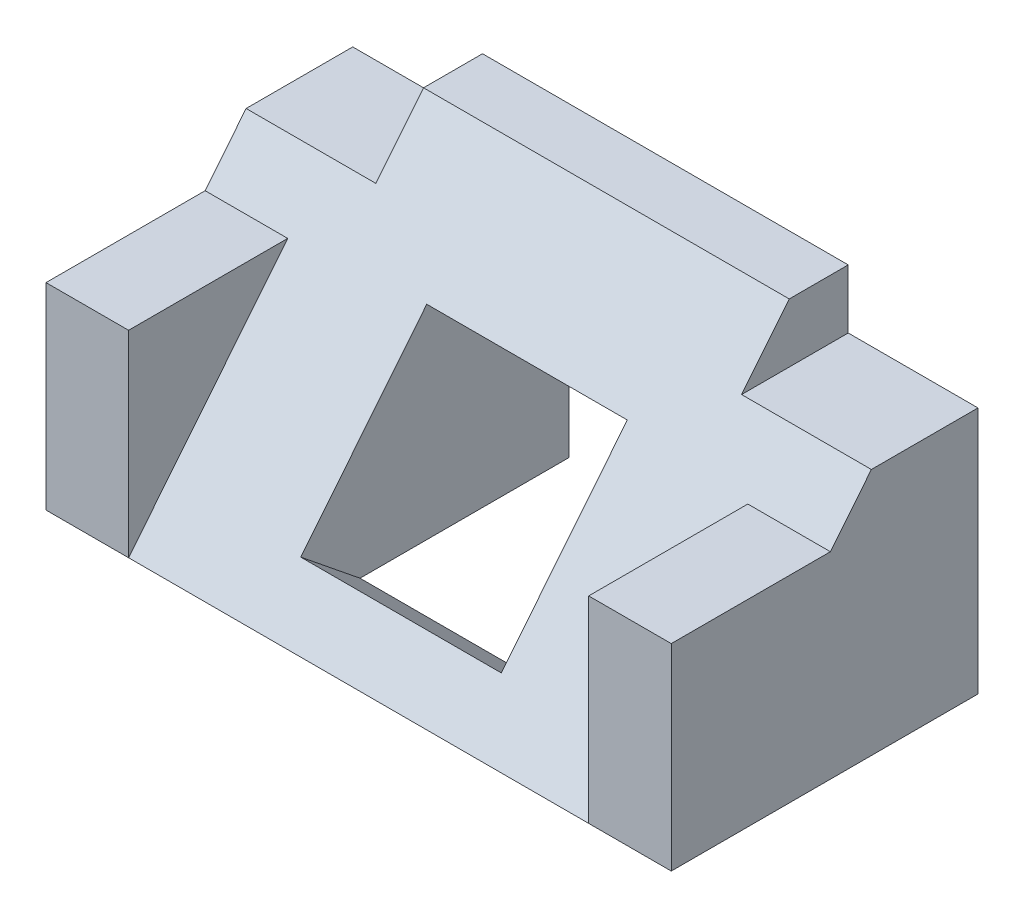
SolidWorks part; units mm, degrees
ref_plane "Front Plane" through (0, 0, 0) normal (0, 0, 1) x (1, 0, 0)
ref_plane "Top Plane" through (0, 0, 0) normal (0, 1, 0) x (1, 0, 0)
ref_plane "Right Plane" through (0, 0, 0) normal (1, 0, 0) x (0, 0, -1)
sketch "Sketch1" plane through (0, 0, 0) normal (1, 0, 0) x (0, 0, -1)
  line L0 (-330.2, -266.7) -> (203.2, 393.7)
  line L1 (100.6231, 266.7) -> (330.2, 266.7)
  line L3 (-330.2, -266.7) -> (330.2, -266.7)
  line L4 (330.2, 266.7) -> (330.2, -266.7)
  line L7 (203.2, 393.7) -> (330.2, 393.7)
  line L9 (203.2, 266.7) -> (330.2, 266.7)
  line L10 (330.2, 393.7) -> (330.2, 266.7)
  point P0 (0, 0)
  point P6 (266.7, 330.2)
  dimension "D1" = 533.4
  dimension "D2" = 127
  dimension "D3" = 127
  dimension "D4" = 660.4
extrude "Boss-Extrude1" add sketch "Sketch1" along normal blind 1346.2 contours L4 L1 L0 L3 | L10 L7 L0 L1
sketch "Sketch2" plane through (1346.2, 0, 0) normal (1, 0, 0) x (0, 0, -1)
  line L0 (330.2, 393.7) -> (330.2, 266.7)
  line L1 (330.2, 393.7) -> (330.2, -266.7) construction
  line L2 (330.2, 266.7) -> (100.6231, 266.7)
  line L3 (-330.2, -266.7) -> (203.2, 393.7) construction
  line L4 (100.6231, 266.7) -> (203.2, 393.7)
  line L5 (203.2, 393.7) -> (330.2, 393.7)
  dimension "D1" = 127
extrude "Cut-Extrude1" cut sketch "Sketch2" against normal blind 279.4
sketch "Sketch3" plane through (0, 0, 0) normal (-1, 0, 0) x (0, 0, 1)
  line L0 (-330.2, 393.7) -> (-330.2, 266.7)
  line L1 (-330.2, 393.7) -> (-330.2, -266.7) construction
  line L2 (-330.2, 266.7) -> (-100.6231, 266.7)
  line L3 (330.2, -266.7) -> (-203.2, 393.7) construction
  dimension "D1" = 127
extrude "Cut-Extrude2" cut sketch "Sketch3" against normal blind 279.4 and the other way through all
sketch "Sketch5" plane through (1346.2, 0, 0) normal (1, 0, 0) x (0, 0, -1)
  line L1 (330.2, -266.7) -> (-330.2, -266.7)
  line L2 (330.2, -266.7) -> (330.2, 157.48)
  line L3 (330.2, 157.48) -> (-330.2, 157.48)
  line L4 (-330.2, -266.7) -> (-330.2, 157.48)
  line L5 (330.2, -266.7) -> (-330.2, 157.48) construction
  line L6 (330.2, 157.48) -> (-330.2, -266.7) construction
  point P4 (0, -54.61)
  dimension "D1" = 424.18
  dimension "D2" = 660.4
extrude "Boss-Extrude2" add sketch "Sketch5" against normal blind 177.8
sketch "Sketch6" plane through (0, 0, 0) normal (-1, 0, 0) x (0, 0, 1)
  line L1 (-330.2, -266.7) -> (330.2, -266.7)
  line L2 (-330.2, -266.7) -> (-330.2, 157.48)
  line L3 (-330.2, 157.48) -> (330.2, 157.48)
  line L4 (330.2, -266.7) -> (330.2, 157.48)
  line L5 (-330.2, -266.7) -> (330.2, 157.48) construction
  line L6 (-330.2, 157.48) -> (330.2, -266.7) construction
  point P4 (0, -54.61)
  dimension "D1" = 424.18
  dimension "D2" = 660.4
extrude "Boss-Extrude3" add sketch "Sketch6" against normal blind 177.8
sketch "Sketch7" plane through (0, 56.1097, 69.4691) normal (0, 0.6283, 0.7779) x (1, 0, 0)
  line L1 (465.1215, 149.4614) -> (896.9215, 149.4614)
  line L2 (465.1215, 149.4614) -> (465.1215, -282.3386)
  line L3 (465.1215, -282.3386) -> (896.9215, -282.3386)
  line L4 (896.9215, 149.4614) -> (896.9215, -282.3386)
  line L5 (465.1215, 149.4614) -> (896.9215, -282.3386) construction
  line L6 (465.1215, -282.3386) -> (896.9215, 149.4614) construction
  point P0 (681.0215, -66.4386)
  dimension "D1" = 431.8
  dimension "D2" = 431.8
extrude "Cut-Extrude3" cut sketch "Sketch7" against normal blind 660.4 contours L2 L1 L4 L3
